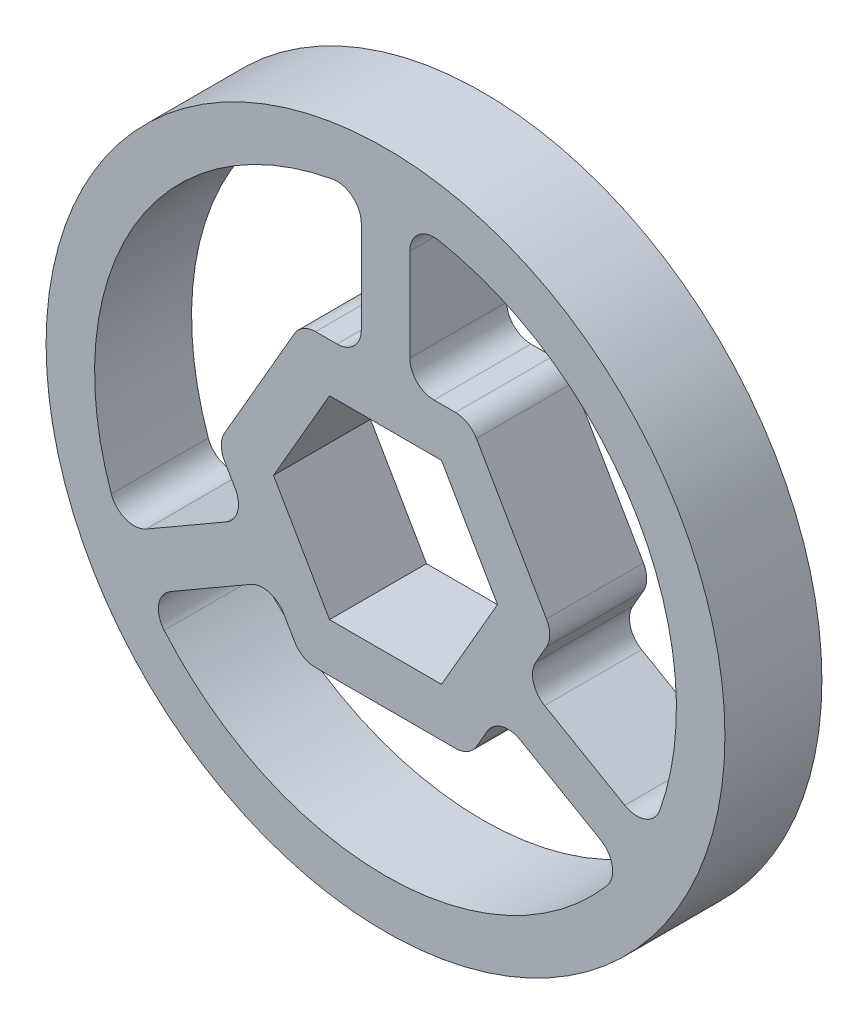
SolidWorks part; units mm, degrees
ref_plane "Front Plane" through (0, 0, 0) normal (0, 0, 1) x (1, 0, 0)
ref_plane "Top Plane" through (0, 0, 0) normal (0, 1, 0) x (1, 0, 0)
ref_plane "Right Plane" through (0, 0, 0) normal (1, 0, 0) x (0, 0, -1)
sketch "Sketch1" plane through (0, 0, 0) normal (0, 0, 1) x (1, 0, 0)
  line L1 (7.3323, 0) -> (3.6662, 6.35)
  line L2 (3.6662, 6.35) -> (-3.6662, 6.35)
  line L3 (-3.6662, 6.35) -> (-7.3323, 0)
  line L4 (-7.3323, 0) -> (-3.6662, -6.35)
  line L5 (-3.6662, -6.35) -> (3.6662, -6.35)
  line L6 (3.6662, -6.35) -> (7.3323, 0)
  line L7 (10.9985, 0) -> (5.4993, 9.525)
  line L8 (5.4993, 9.525) -> (-5.4993, 9.525)
  line L9 (-5.4993, 9.525) -> (-10.9985, 0)
  line L10 (-10.9985, 0) -> (-5.4993, -9.525)
  line L11 (-5.4993, -9.525) -> (5.4993, -9.525)
  line L12 (5.4993, -9.525) -> (10.9985, 0)
  circle A1 centre (0, 0) radius 6.35 construction
  circle A2 centre (0, 0) radius 9.525 construction
  circle A3 centre (0, 0) radius 19.05
  circle A4 centre (0, 0) radius 22.225
  dimension "D1" = 44.45
  dimension "D2" = 12.7
  dimension "D3" = 19.05
  dimension "D4" = 38.1
extrude "Boss-Extrude1" add sketch "Sketch1" along normal blind 6.35 contours A4 A3 | L11 L12 L7 L8 L9 L10 L6 L5 L4 L3 L2 L1
sketch "Sketch4" plane through (0, 0, 0) normal (0, 0, 1) x (1, 0, 0)
  line L0 (0, 19.05) -> (0, 9.525) construction
  line L1 (5.4993, 9.525) -> (-5.4993, 9.525) construction
  line L2 (-1.5875, 18.9837) -> (-1.5875, 9.525)
  line L3 (-1.5875, 9.525) -> (1.5875, 9.525)
  line L4 (1.5875, 9.525) -> (1.5875, 18.9837)
  circle A0 centre (0, 0) radius 19.05 construction
  arc A1 (-1.5875, 18.9837) -> (1.5875, 18.9837) centre (0, 0) cw
  dimension "D1" = 3.175
extrude "Boss-Extrude2" add sketch "Sketch4" along normal up to surface (6.35 mm away) up to face at (0, 0, 6.35)
pattern_circular "CirPattern1" count 3 over 360 about axis through (0, 0, 0) along (0, 0, 1) of "Boss-Extrude2"
fillet "Fillet2" radius 1.5875 18 edges at (15.6467, -10.8667, 3.175) (7.4551, -6.1373, 3.175) (5.4993, -9.525, 3.175) (-7.4551, -6.1373, 3.175) (-5.4993, -9.525, 3.175) (-15.6467, -10.8667, 3.175) (-17.2342, -8.1171, 3.175) (-10.9985, 0, 3.175) (-9.0426, -3.3877, 3.175) (-5.4993, 9.525, 3.175) (-1.5875, 9.525, 3.175) (-1.5875, 18.9837, 3.175) (1.5875, 18.9837, 3.175) (1.5875, 9.525, 3.175) (5.4993, 9.525, 3.175) (10.9985, 0, 3.175) (9.0426, -3.3877, 3.175) (17.2342, -8.1171, 3.175)
